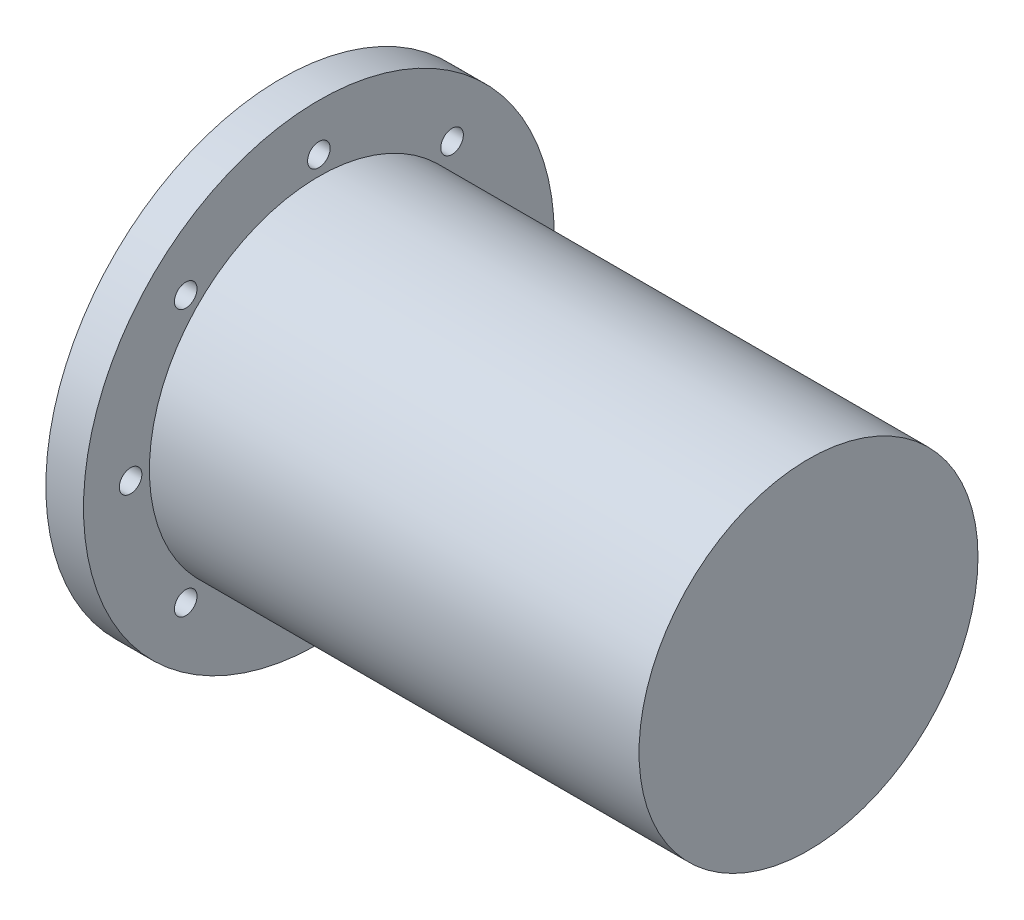
SolidWorks part; units mm, degrees
ref_plane "Alzado" through (0, 0, 0) normal (0, 0, 1) x (1, 0, 0)
ref_plane "Planta" through (0, 0, 0) normal (0, 1, 0) x (1, 0, 0)
ref_plane "Vista lateral" through (0, 0, 0) normal (1, 0, 0) x (0, 0, -1)
sketch "Croquis1" plane through (0, 0, 0) normal (1, 0, 0) x (0, 0, -1)
  line L0 (0, 0) -> (0, -100) construction
  circle A0 centre (0, 0) radius 125
  circle A1 centre (0, -100) radius 6
  circle A2 centre (-70.7107, -70.7107) radius 6
  circle A3 centre (-100, 0) radius 6
  circle A4 centre (-70.7107, 70.7107) radius 6
  circle A5 centre (0, 100) radius 6
  circle A6 centre (70.7107, 70.7107) radius 6
  circle A7 centre (100, 0) radius 6
  circle A8 centre (70.7107, -70.7107) radius 6
  point P22 (0, 0)
  dimension "D1" = 250
  dimension "D2" = 12
  dimension "D3" = 100
  dimension "D4" = 8
extrude "Saliente-Extruir1" add sketch "Croquis1" along normal blind 20
sketch "Croquis2" plane through (20, 0, 0) normal (1, 0, 0) x (0, 0, -1)
  circle A0 centre (0, 0) radius 90
  dimension "D1" = 180
extrude "Saliente-Extruir2" add sketch "Croquis2" along normal blind 260
